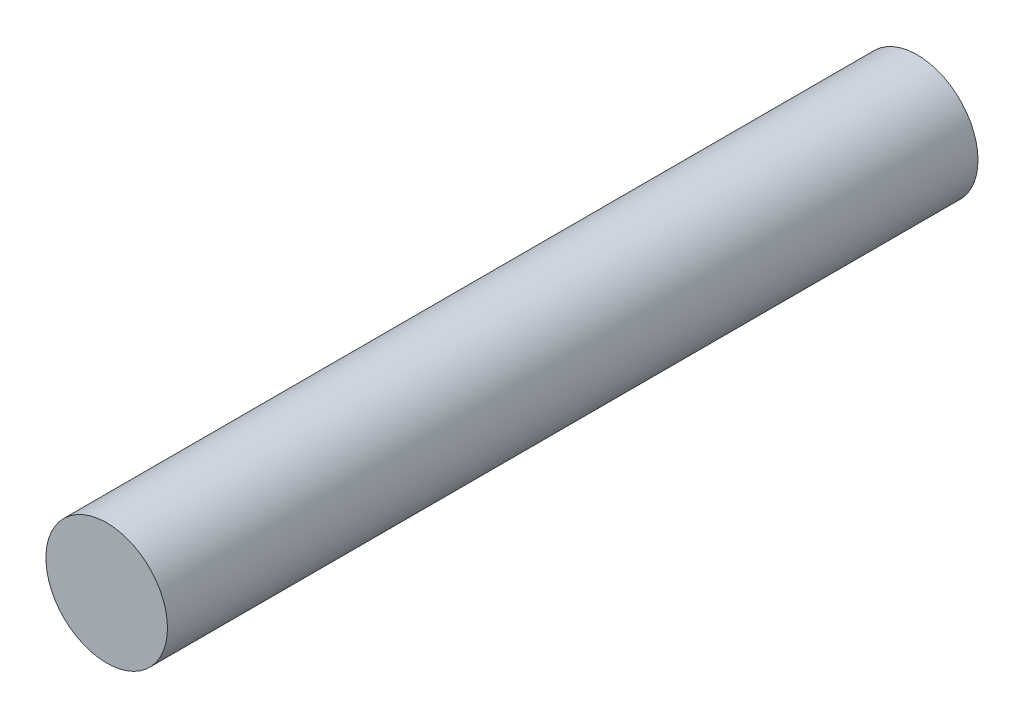
SolidWorks part; units mm, degrees
ref_plane "Front Plane" through (0, 0, 0) normal (0, 0, 1) x (1, 0, 0)
ref_plane "Top Plane" through (0, 0, 0) normal (0, 1, 0) x (1, 0, 0)
ref_plane "Right Plane" through (0, 0, 0) normal (1, 0, 0) x (0, 0, -1)
sketch "Sketch2" plane through (0, 0, 0) normal (0, 0, 1) x (1, 0, 0)
  circle A0 centre (0, 0) radius 3.75
  dimension "D1" = 7.5
extrude "Boss-Extrude1" add sketch "Sketch2" along normal blind 50 contours A0
